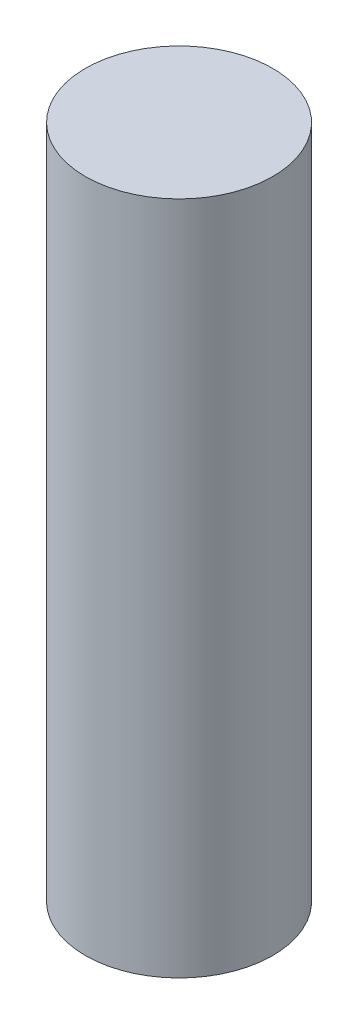
SolidWorks part; units mm, degrees
ref_plane "Front Plane" through (0, 0, 0) normal (0, 0, 1) x (1, 0, 0)
ref_plane "Top Plane" through (0, 0, 0) normal (0, 1, 0) x (1, 0, 0)
ref_plane "Right Plane" through (0, 0, 0) normal (1, 0, 0) x (0, 0, -1)
sketch "Sketch1" plane through (0, 0, 0) normal (0, 1, 0) x (1, 0, 0)
  circle A0 centre (0, 0) radius 12.7
  dimension "D1" = 25.4
extrude "Boss-Extrude1" add sketch "Sketch1" along normal blind 66.04
sketch "Sketch2" plane through (0, 66.04, 0) normal (0, 1, 0) x (1, 0, 0)
  circle A0 centre (0, 0) radius 12.7
extrude "Boss-Extrude2" add sketch "Sketch2" along normal blind 25.4
